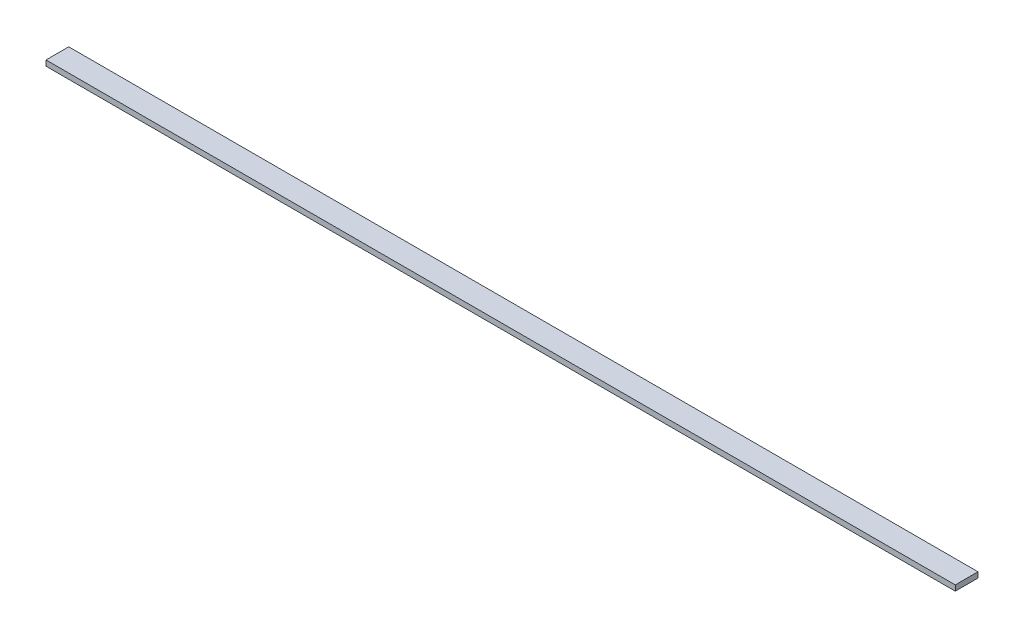
SolidWorks part; units mm, degrees
ref_plane "Front Plane" through (0, 0, 0) normal (0, 0, 1) x (1, 0, 0)
ref_plane "Top Plane" through (0, 0, 0) normal (0, 1, 0) x (1, 0, 0)
ref_plane "Right Plane" through (0, 0, 0) normal (1, 0, 0) x (0, 0, -1)
sketch "Sketch1" plane through (0, 0, 0) normal (0, 1, 0) x (1, 0, 0)
  line L1 (-75.9433, 31.6632) -> (924.0567, 31.6632)
  line L2 (-75.9433, 31.6632) -> (-75.9433, 6.6632)
  line L3 (-75.9433, 6.6632) -> (924.0567, 6.6632)
  line L4 (924.0567, 31.6632) -> (924.0567, 6.6632)
  dimension "D1" = 25
  dimension "D2" = 1000
extrude "Boss-Extrude1" add sketch "Sketch1" along normal blind 6
